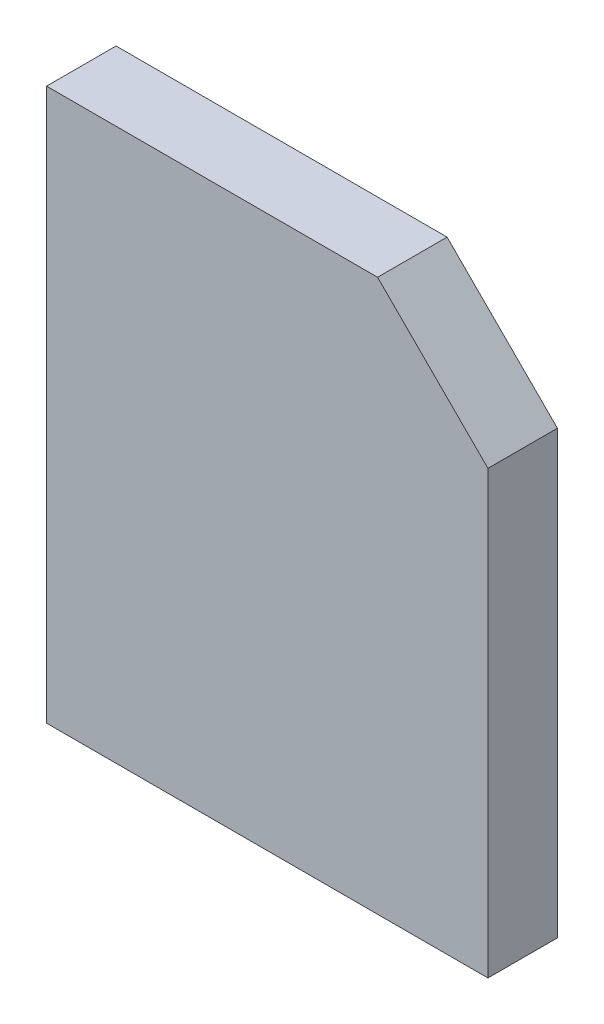
SolidWorks part; units mm, degrees
ref_plane "1" through (0, 0, 0) normal (0, 0, 1) x (1, 0, 0)
ref_plane "2" through (0, 0, 0) normal (0, 1, 0) x (1, 0, 0)
ref_plane "3" through (0, 0, 0) normal (1, 0, 0) x (0, 0, -1)
ref_plane "Front Plane" through (0, 0, 0) normal (0, -1, 0) x (1, 0, 0)
ref_plane "Right Plane" through (0, 0, 0) normal (1, 0, 0) x (0, 1, 0)
ref_plane "Top Plane" through (0, 0, 0) normal (0, 0, 1) x (1, 0, 0)
ref_plane "Plane1" through (0, 0, 2.3) normal (0, 0, 1) x (1, 0, 0)
sketch "Sketch1" plane through (0, 0, 0) normal (0, 0, 1) x (1, 0, 0)
  line L0 (-5.08, 6.35) -> (5.08, 6.35) construction
  line L1 (-5.08, 6.35) -> (-5.08, -6.35) construction
  line L2 (5.08, 6.35) -> (5.08, -6.35) construction
  line L3 (-5.08, -6.35) -> (5.08, -6.35) construction
  line L4 (0, 6.35) -> (0, 5.152) construction
  line L5 (5.08, 0) -> (24.8253, 0) construction
  dimension "D1" = 10.16
  dimension "D2" = 12.7
sketch "Sketch2" plane through (0, 0, 2.3) normal (0, 0, 1) x (1, 0, 0)
  line L8 (-5.08, -6.35) -> (5.08, -6.35)
  line L9 (-5.08, -6.35) -> (-5.08, 6.35)
  line L10 (5.08, -6.35) -> (5.08, 3.81)
  line L11 (-5.08, 6.35) -> (2.54, 6.35)
  line L12 (5.08, 3.81) -> (2.54, 6.35)
  line L13 (-5.08, 6.35) -> (5.08, 6.35) construction
  line L14 (-5.08, 6.35) -> (-5.08, -6.35) construction
  line L15 (-5.08, -6.35) -> (5.08, -6.35) construction
  line L16 (5.08, 6.35) -> (5.08, -6.35) construction
  point P4 (5.08, 6.35)
extrude "Boss-Extrude1" add sketch "Sketch2" along normal blind 1.6
